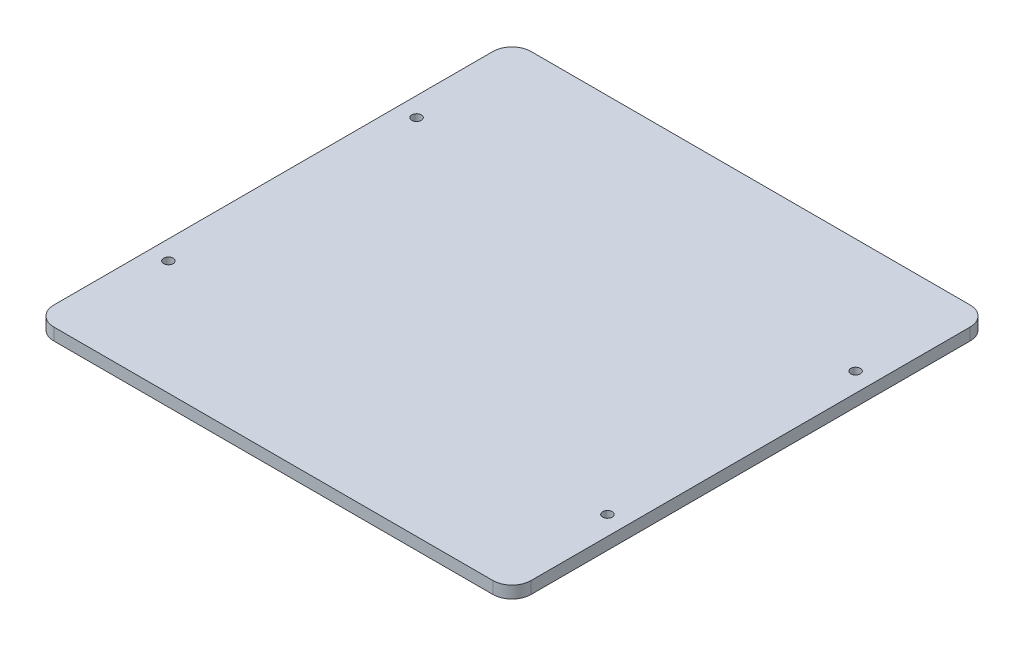
SolidWorks part; units mm, degrees
ref_plane "Front Plane" through (0, 0, 0) normal (0, 0, 1) x (1, 0, 0)
ref_plane "Top Plane" through (0, 0, 0) normal (0, 1, 0) x (1, 0, 0)
ref_plane "Right Plane" through (0, 0, 0) normal (1, 0, 0) x (0, 0, -1)
sketch "Sketch1" plane through (0, 0, 0) normal (0, 1, 0) x (1, 0, 0)
  line L0 (-125, 0) -> (125, 0) construction
  line L1 (-125, 125) -> (125, 125)
  line L2 (-125, 125) -> (-125, -125)
  line L3 (-125, -125) -> (125, -125)
  line L4 (125, 125) -> (125, -125)
  point P6 (0, 0)
  dimension "D1" = 250
extrude "Boss-Extrude1" add sketch "Sketch1" along normal blind 6.35
sketch "Sketch2" plane through (0, 6.35, 0) normal (0, 1, 0) x (1, 0, 0)
  line L0 (-115, 65) -> (115, 65) construction
  line L1 (115, 65) -> (-115, -65) construction
  line L2 (-115, -65) -> (115, -65) construction
  line L3 (115, 65) -> (115, -65) construction
  line L4 (-115, 65) -> (-115, -65) construction
  line L6 (125, -125) -> (125, 125) construction
  circle A0 centre (-115, 65) radius 2.5
  circle A1 centre (115, 65) radius 2.5
  circle A2 centre (115, -65) radius 2.5
  circle A3 centre (-115, -65) radius 2.5
  point P4 (0, 0)
  dimension "D2" = 5
  dimension "D1" = 10
  dimension "D3" = 130
extrude "Cut-Extrude1" cut sketch "Sketch2" against normal through all
fillet "Fillet1" radius 10 4 edges at (-125, 3.175, -125) (125, 3.175, -125) (125, 3.175, 125) (-125, 3.175, 125)
